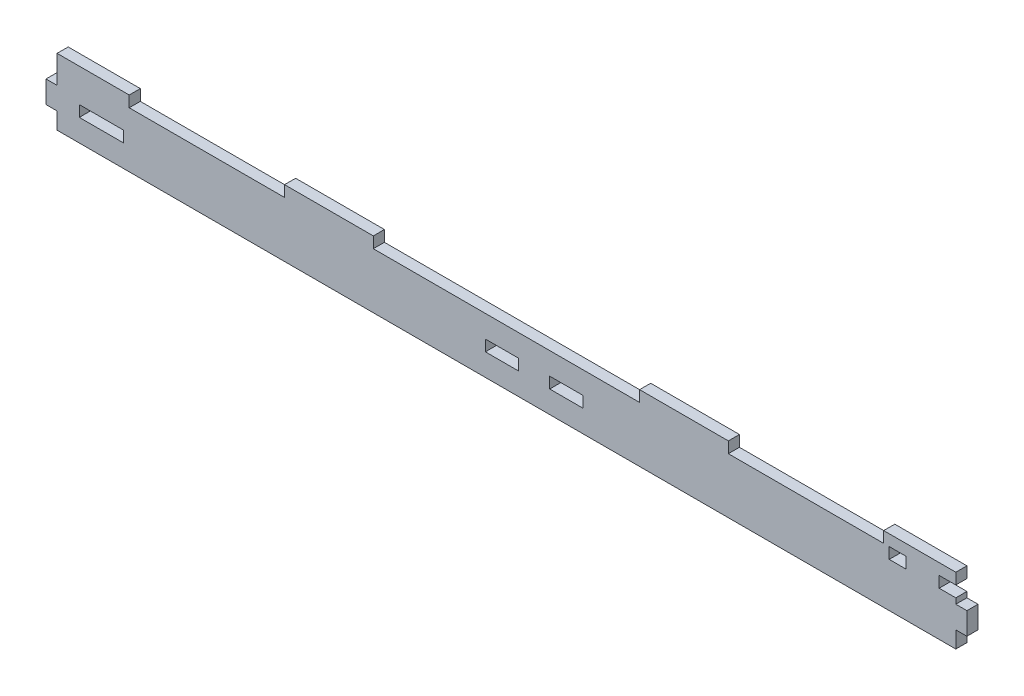
SolidWorks part; units mm, degrees
ref_plane "Front Plane" through (0, 0, 0) normal (0, 0, 1) x (1, 0, 0)
ref_plane "Top Plane" through (0, 0, 0) normal (0, 1, 0) x (1, 0, 0)
ref_plane "Right Plane" through (0, 0, 0) normal (1, 0, 0) x (0, 0, -1)
sketch "Sketch1" plane through (0, 0, 0) normal (0, 0, 1) x (1, 0, 0)
  line L0 (252.5, 195) -> (252.5, 170) construction
  line L1 (277.5, 254.5874) -> (277.5, 116.6829) construction
  line L8 (480, 177.5) -> (485, 177.5)
  line L9 (480, 170) -> (480, 177.5)
  line L11 (447.5, 195) -> (377.5, 195)
  line L12 (480, 190) -> (480, 187.5)
  line L13 (480, 187.5) -> (485, 187.5)
  line L14 (485, 187.5) -> (485, 177.5)
  line L15 (377.5, 200) -> (377.5, 195)
  line L16 (337.5, 200) -> (377.5, 200)
  line L17 (337.5, 195) -> (337.5, 200)
  line L18 (480, 200) -> (480, 195)
  line L19 (447.5, 200) -> (480, 200)
  line L20 (447.5, 195) -> (447.5, 200)
  line L21 (435, 192.1418) -> (435, 212.7842) construction
  line L22 (217.5, 195) -> (337.5, 195)
  line L25 (107.5, 195) -> (107.5, 200)
  line L26 (107.5, 200) -> (75, 200)
  line L27 (75, 200) -> (75, 195)
  line L29 (217.5, 195) -> (217.5, 200)
  line L30 (217.5, 200) -> (177.5, 200)
  line L31 (177.5, 200) -> (177.5, 195)
  line L40 (70, 187.5) -> (70, 177.5)
  line L43 (75, 187.5) -> (70, 187.5)
  line L48 (430, 182.5) -> (424.9156, 182.5) construction
  line L49 (75, 195) -> (75, 187.5)
  line L50 (107.5, 195) -> (177.5, 195)
  line L58 (75, 170) -> (75, 177.5)
  line L60 (75, 177.5) -> (70, 177.5)
  line L73 (480, 170) -> (75, 170)
  line L75 (450, 195) -> (457.5, 195)
  line L76 (450, 195) -> (450, 190)
  line L77 (450, 190) -> (457.5, 190)
  line L78 (457.5, 195) -> (457.5, 190)
  line L79 (472.5, 195) -> (480, 195)
  line L80 (472.5, 195) -> (472.5, 190)
  line L81 (85, 180) -> (105, 180)
  line L82 (105, 180) -> (105, 185)
  line L83 (105, 185) -> (85, 185)
  line L84 (85, 185) -> (85, 180)
  line L85 (472.5, 190) -> (480, 190)
  line L89 (312, 185) -> (297, 185)
  line L90 (297, 185) -> (297, 180)
  line L91 (297, 180) -> (312, 180)
  line L92 (312, 180) -> (312, 185)
  line L93 (283, 185) -> (268, 185)
  line L94 (268, 185) -> (268, 180)
  line L95 (268, 180) -> (283, 180)
  line L96 (283, 180) -> (283, 185)
  point P33 (70, 182.5)
  point P47 (485, 182.5)
  dimension "D1" = 25
extrude "Boss-Extrude1" add sketch "Sketch1" along normal blind 5
